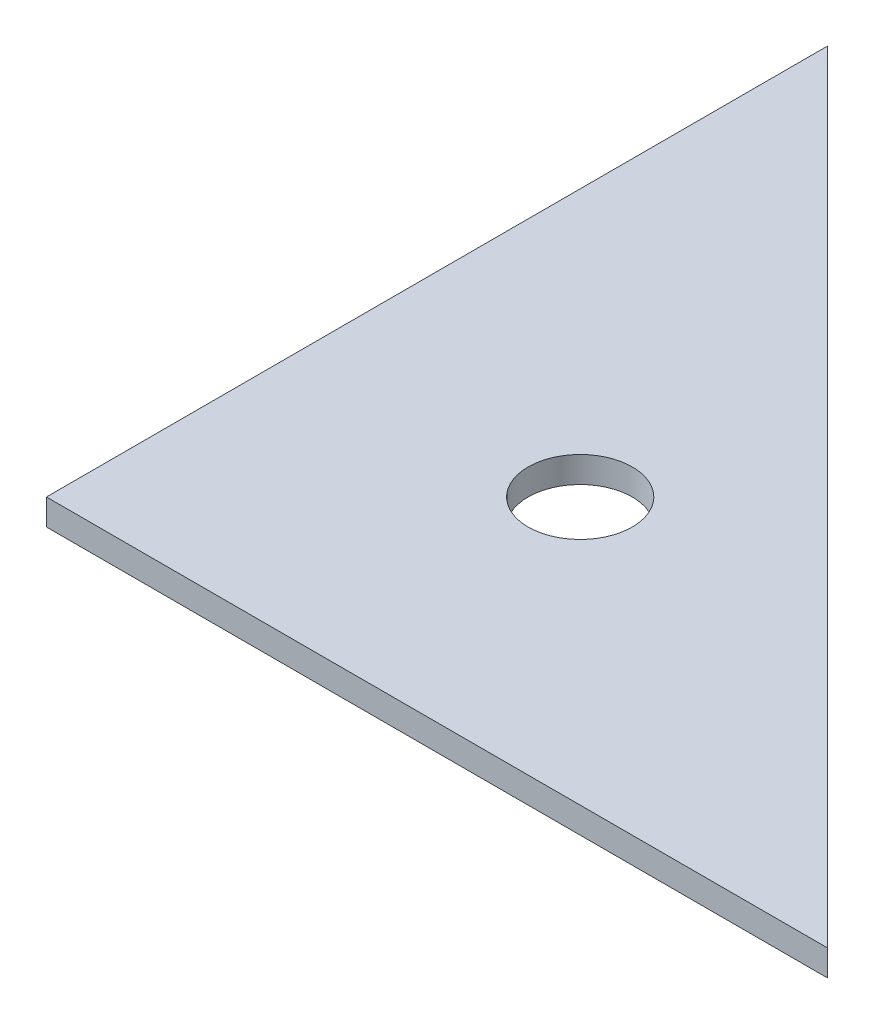
SolidWorks part; units mm, degrees
material "Galvanized Steel"
ref_plane "Front Plane" through (0, 0, 0) normal (0, 0, 1) x (1, 0, 0)
ref_plane "Top Plane" through (0, 0, 0) normal (0, 1, 0) x (1, 0, 0)
ref_plane "Right Plane" through (0, 0, 0) normal (1, 0, 0) x (0, 0, -1)
sketch "Sketch1" plane through (0, 0, 0) normal (0, 1, 0) x (1, 0, 0)
  line L0 (0, 0) -> (60, 0)
  line L1 (0, 0) -> (0, 60)
  line L2 (0, 60) -> (60, 0)
  circle A0 centre (20.5, 20.5) radius 4
  dimension "D1" = 20.5
  dimension "D2" = 20.5
extrude "Boss-Extrude1" add sketch "Sketch1" along normal blind 2
